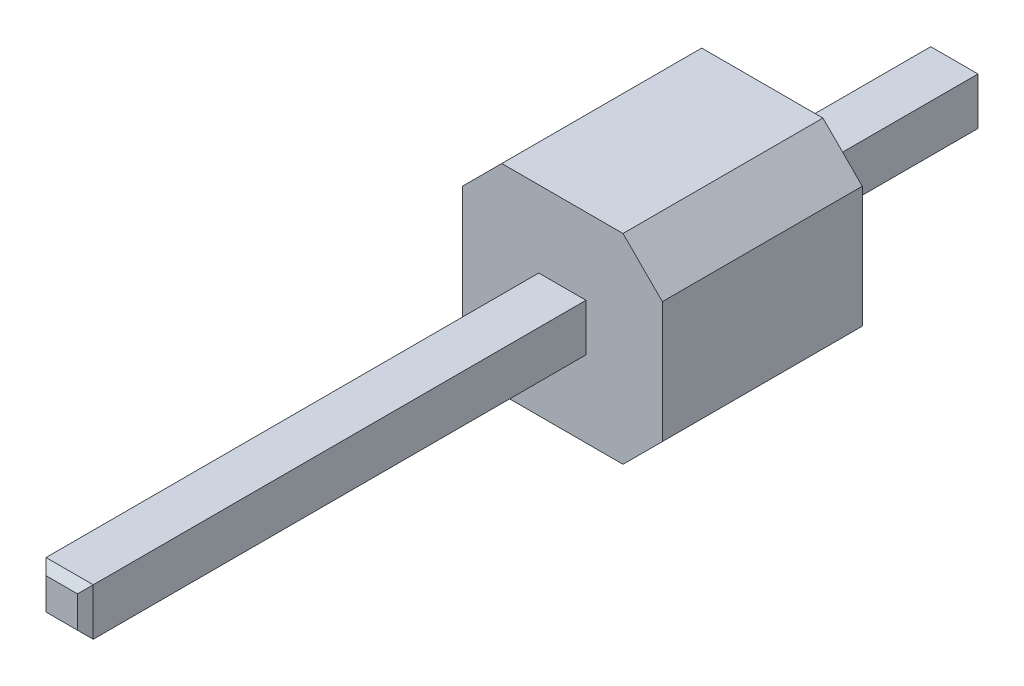
SolidWorks part; units mm, degrees
ref_plane "Front Plane" through (0, 0, 0) normal (0, 0, 1) x (1, 0, 0)
ref_plane "Top Plane" through (0, 0, 0) normal (0, 1, 0) x (1, 0, 0)
ref_plane "Right Plane" through (0, 0, 0) normal (1, 0, 0) x (0, 0, -1)
sketch "Sketch1" plane through (0, 0, 0) normal (0, 0, 1) x (1, 0, 0)
  line L0 (1.27, 0) -> (0, 0) construction
  line L5 (0, 0) -> (0, 1.27) construction
  line L6 (-0.77, 1.27) -> (0.77, 1.27)
  line L7 (0.77, 1.27) -> (1.27, 0.77)
  line L8 (1.27, 0.77) -> (1.27, -0.77)
  line L9 (-1.27, 0.77) -> (-1.27, -0.77)
  line L10 (-0.77, 1.27) -> (-1.27, 0.77)
  line L11 (0.77, -1.27) -> (1.27, -0.77)
  line L12 (-0.77, -1.27) -> (0.77, -1.27)
  line L13 (-0.77, -1.27) -> (-1.27, -0.77)
  point P4 (0, 0)
  point P13 (-1.27, 0)
  point P14 (0, 0)
  point P15 (0, 0)
  point P16 (-1.3282, 0.0309)
  point P17 (0, 0)
  dimension "D1" = 1.27
  dimension "D2" = 45
  dimension "D3" = 0.5
extrude "Plastic" add sketch "Sketch1" along normal blind 2.54
sketch "Sketch2" plane through (0, 0, 0) normal (1, 0, 0) x (0, 0, -1)
  line L0 (-8.9, 0.3) -> (-8.9, -0.3)
  line L1 (-8.9, 0) -> (2.54, 0) construction
  line L4 (-8.9, -0.3) -> (2.54, -0.3)
  line L6 (-8.9, 0.3) -> (2.54, 0.3)
  line L8 (2.54, -0.3) -> (2.54, 0.3)
  line L11 (-9.5, 4.63) -> (-9.5, 0.6) construction
  line L12 (-9.8, 4.63) -> (-9.8, 0.6) construction
  line L13 (-9.2, 4.63) -> (-9.2, 0.6) construction
  arc A3 (-9.8, 0.6) -> (-8.9, -0.3) centre (-8.9, 0.6) ccw construction
  arc A4 (-9.5, 0.6) -> (-8.9, 0) centre (-8.9, 0.6) ccw construction
  arc A5 (-9.2, 0.6) -> (-8.9, 0.3) centre (-8.9, 0.6) ccw construction
  point P6 (0, 0)
  point P22 (0.5758, 0.2967)
  point P30 (0.5805, 0.1553)
  dimension "D1" = 8.9
  dimension "D4" = 2.54
  dimension "D2" = 0.3
  dimension "D3" = 0.3
extrude "Contact" add sketch "Sketch2" along normal mid plane 0.6
chamfer "Chamfer1" distance 0.1 angle 45 8 edges at (0.3, 0, -2.54) (0, -0.3, -2.54) (-0.3, 0, -2.54) (0, 0.3, -2.54) (-0.3, 0, 8.9) (0, 0.3, 8.9) (0.3, 0, 8.9) (0, -0.3, 8.9)
